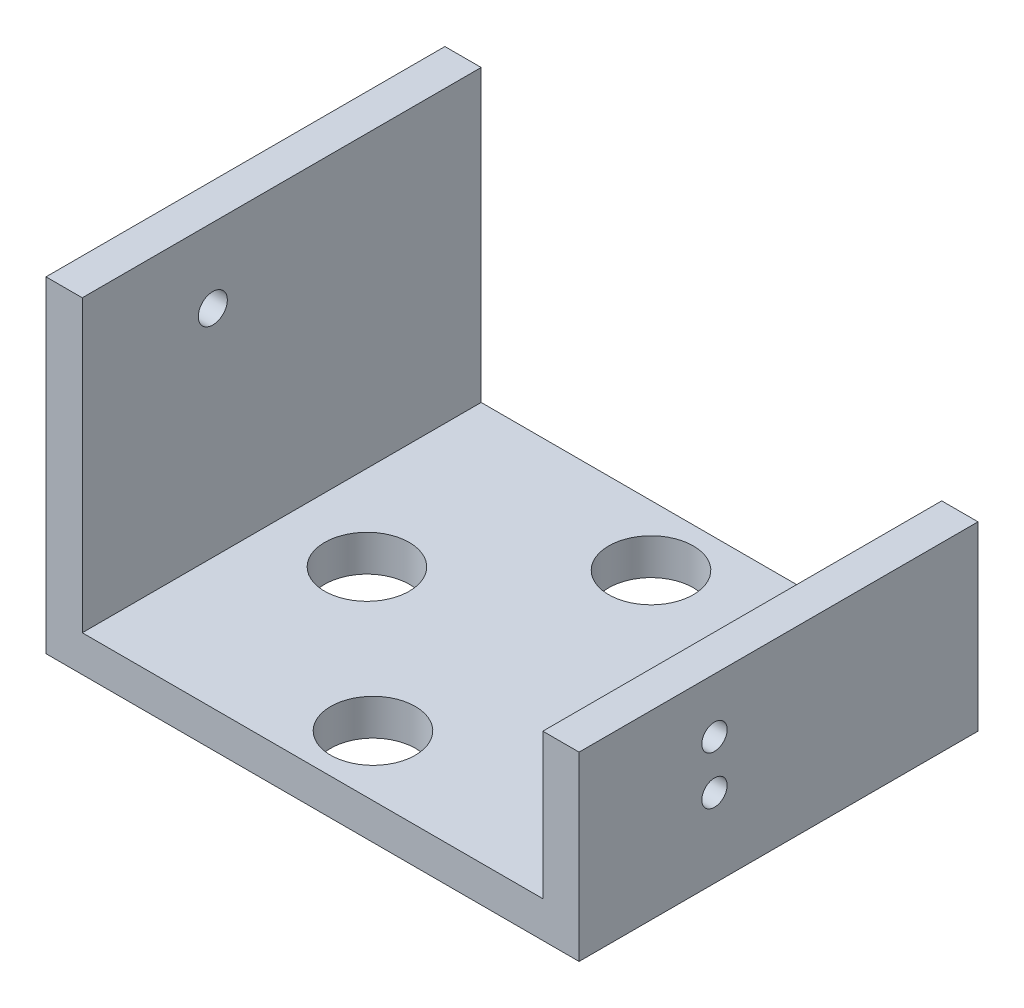
SolidWorks part; units mm, degrees
ref_plane "Ebene vorne" through (0, 0, 0) normal (0, 0, 1) x (1, 0, 0)
ref_plane "Ebene oben" through (0, 0, 0) normal (0, 1, 0) x (1, 0, 0)
ref_plane "Ebene rechts" through (0, 0, 0) normal (1, 0, 0) x (0, 0, -1)
sketch "Skizze1" plane through (0, 0, 0) normal (0, 1, 0) x (1, 0, 0)
  line L1 (-22.05, -16.5) -> (22.05, -16.5)
  line L2 (-22.05, -16.5) -> (-22.05, 16.5)
  line L3 (-22.05, 16.5) -> (22.05, 16.5)
  line L4 (22.05, -16.5) -> (22.05, 16.5)
  line L5 (-22.05, -16.5) -> (22.05, 16.5) construction
  line L6 (-22.05, 16.5) -> (22.05, -16.5) construction
  point P0 (0, 0)
  dimension "D1" = 44.1
  dimension "D2" = 33
extrude "Aufsatz-Linear austragen1" add sketch "Skizze1" along normal blind 3
sketch "Skizze2" plane through (0, 3, 0) normal (0, 1, 0) x (1, 0, 0)
  line L0 (-22.05, -16.5) -> (22.05, -16.5) construction
  line L1 (-22.05, 16.5) -> (-19.05, 16.5)
  line L2 (-22.05, 16.5) -> (-22.05, -16.5)
  line L3 (-22.05, -16.5) -> (-19.05, -16.5)
  line L4 (-19.05, 16.5) -> (-19.05, -16.5)
  line L5 (22.05, 16.5) -> (-22.05, 16.5) construction
  line L6 (22.05, -16.5) -> (19.05, -16.5)
  line L7 (22.05, -16.5) -> (22.05, 16.5)
  line L8 (22.05, 16.5) -> (19.05, 16.5)
  line L9 (19.05, -16.5) -> (19.05, 16.5)
  dimension "D1" = 3
  dimension "D2" = 3
extrude "Aufsatz-Linear austragen2" add sketch "Skizze2" along normal blind 24
sketch "Skizze3" plane through (22.05, 0, 0) normal (1, 0, 0) x (0, 0, -1)
  line L0 (16.5, 27) -> (16.5, 0) construction
  line L1 (-16.5, 27) -> (16.5, 27)
  line L2 (-16.5, 27) -> (-16.5, 15)
  line L3 (-16.5, 15) -> (16.5, 15)
  line L4 (16.5, 27) -> (16.5, 15)
  dimension "D1" = 12
extrude "Schnitt-Linear austragen1" cut sketch "Skizze3" against normal blind 24
sketch "Skizze4" plane through (-19.05, 0, 0) normal (1, 0, 0) x (0, 0, -1)
  circle A0 centre (-5.7, 20.85) radius 1.2
extrude "Schnitt-Linear austragen2" cut sketch "Skizze4" against normal blind 10
sketch "Skizze5" plane through (22.05, 0, 0) normal (1, 0, 0) x (0, 0, -1)
  line L0 (-5.3, 14.7) -> (-5.3, 0) construction
  line L1 (-16.5, 14.7) -> (16.5, 14.7) construction
  line L2 (-16.5, 0) -> (16.5, 0) construction
  line L3 (-16.5, 15) -> (-16.5, 0) construction
  line L4 (16.5, 29.5) -> (-16.5, 29.5) construction
  circle A0 centre (-5.3, 10.5) radius 1.05
  circle A1 centre (-5.3, 6.5) radius 1.05
  dimension "D2" = 2.1
  dimension "D4" = 2.1
  dimension "D1" = 11.2
  dimension "D3" = 19
  dimension "D5" = 23
extrude "Schnitt-Linear austragen3" cut sketch "Skizze5" against normal blind 10
sketch "Skizze6" plane through (0, 0, 0) normal (0, -1, 0) x (1, 0, 0)
  line L0 (0, 16.5) -> (0, -16.5) construction
  line L2 (22.05, -16.5) -> (-22.05, -16.5) construction
  line L3 (0, -16.5) -> (22.05, 0) construction
  line L4 (22.05, 16.5) -> (22.05, -16.5) construction
  line L5 (22.05, 0) -> (-22.05, 0) construction
  line L6 (-22.05, -16.5) -> (-22.05, 16.5) construction
  line L7 (-22.05, 16.5) -> (22.05, 16.5) construction
  circle A0 centre (-12, 0) radius 3.5
  circle A1 centre (0, -11.5) radius 3.5
  circle A2 centre (12, 0) radius 3.5
  circle A4 centre (0, 11.5) radius 3.5
  dimension "D1" = 7
  dimension "D2" = 7
  dimension "D3" = 7
  dimension "D4" = 7
  dimension "D5" = 12
  dimension "D6" = 12
  dimension "D7" = 5
  dimension "D8" = 5
extrude "Schnitt-Linear austragen4" cut sketch "Skizze6" against normal blind 10
